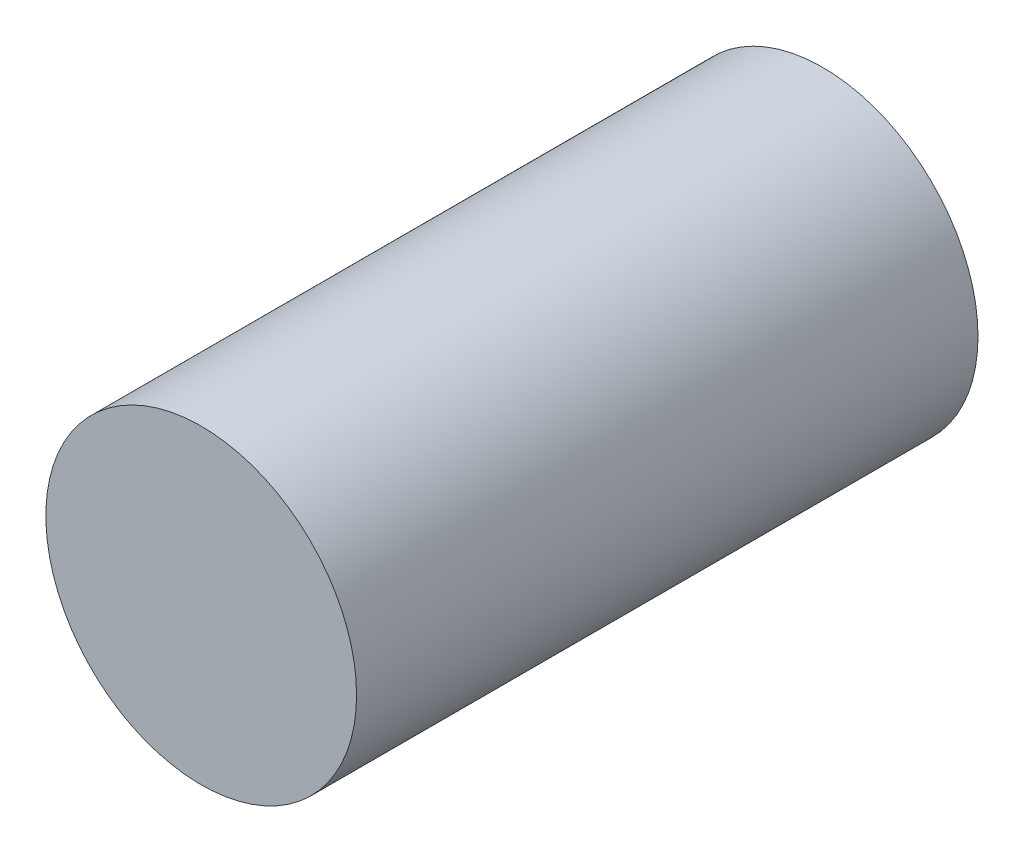
SolidWorks part; units mm, degrees
ref_plane "Спереди" through (0, 0, 0) normal (0, 0, 1) x (1, 0, 0)
ref_plane "Сверху" through (0, 0, 0) normal (0, 1, 0) x (1, 0, 0)
ref_plane "Справа" through (0, 0, 0) normal (1, 0, 0) x (0, 0, -1)
sketch "Эскиз1" plane through (0, 0, 0) normal (0, 0, 1) x (1, 0, 0)
  circle A0 centre (0, 0) radius 10
extrude "Бобышка-Вытянуть1" add sketch "Эскиз1" along normal blind 40
